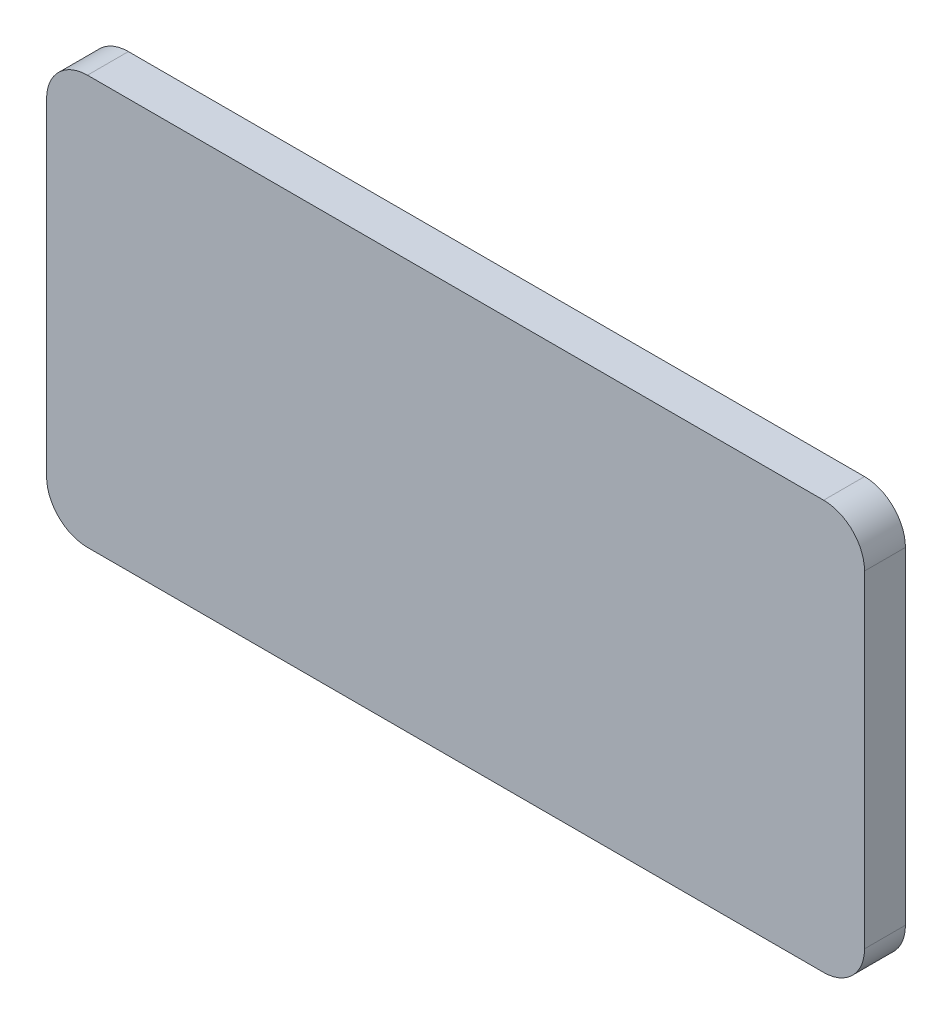
SolidWorks part; units mm, degrees
ref_plane "Front Plane" through (0, 0, 0) normal (0, 0, 1) x (1, 0, 0)
ref_plane "Top Plane" through (0, 0, 0) normal (0, 1, 0) x (1, 0, 0)
ref_plane "Right Plane" through (0, 0, 0) normal (1, 0, 0) x (0, 0, -1)
sketch "Esquisse1" plane through (0, 0, 0) normal (0, 0, 1) x (1, 0, 0)
  line L1 (0, 0) -> (-100, 0)
  line L2 (0, 0) -> (0, -50)
  line L3 (0, -50) -> (-100, -50)
  line L4 (-100, 0) -> (-100, -50)
  line L5 (-50, -50) -> (-50, 0) construction
  line L6 (0, -25) -> (-100, -25) construction
  point P96 (-50, -25)
  dimension "D1" = 50
  dimension "D2" = 100
extrude "Boss.-Extru.1" add sketch "Esquisse1" along normal blind 5
fillet "Congé2" radius 5 4 edges at (0, -50, 2.5) (-100, -50, 2.5) (0, 0, 2.5) (-100, 0, 2.5)
